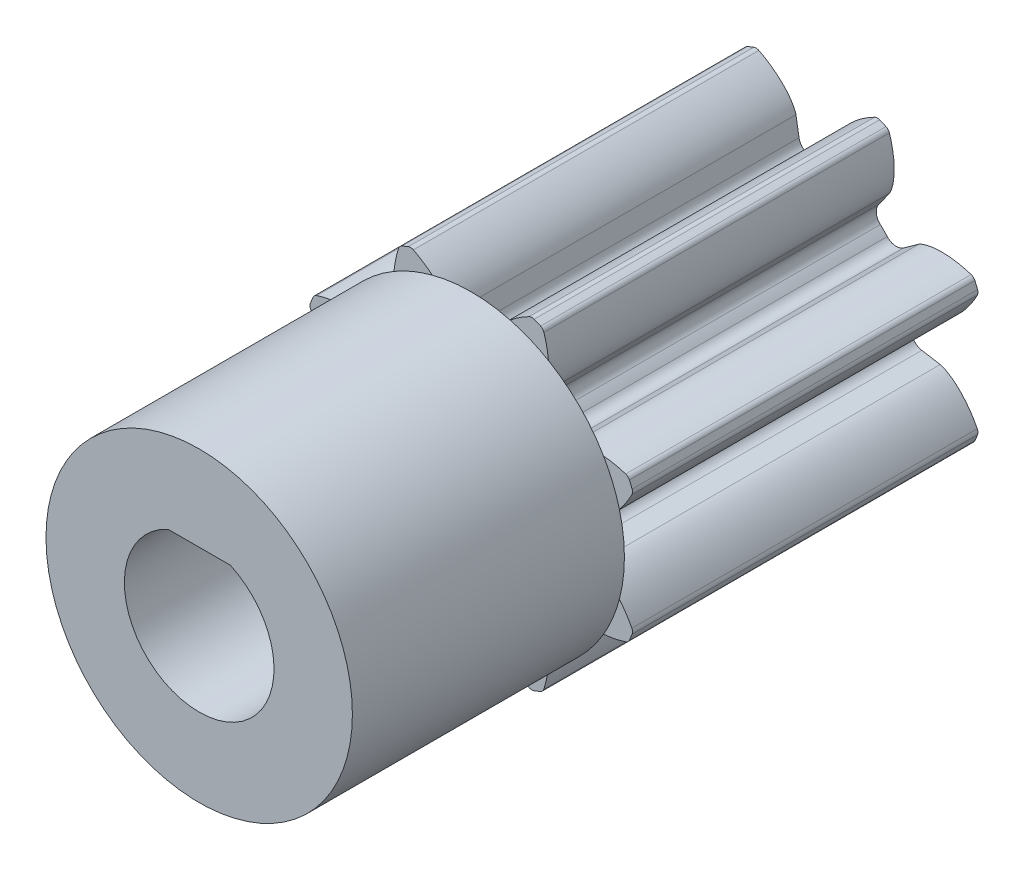
SolidWorks part; units mm, degrees
material "Alloy Steel"
ref_plane "Front" through (0, 0, 0) normal (0, 0, 1) x (1, 0, 0)
ref_plane "Top" through (0, 0, 0) normal (0, 1, 0) x (1, 0, 0)
ref_plane "Right" through (0, 0, 0) normal (1, 0, 0) x (0, 0, -1)
sketch "Sketch1" plane through (0, 0, 0) normal (0, 0, 1) x (1, 0, 0)
  circle A0 centre (0, 0) radius 6.35
extrude "Boss-Extrude1" add sketch "Sketch1" along normal blind 12.7
sketch "Sketch3" plane through (0, 0, 0) normal (0, 0, 1) x (1, 0, 0)
  line L0 (0, 0) -> (43.7181, 0) construction
  line L2 (0, 0) -> (-0.5784, 3.4443) construction
  line L3 (0, 0) -> (0.5784, 3.4443) construction
  line L4 (0.5784, 3.4443) -> (0.7625, 4.5405) construction
  line L5 (0, 0) -> (0, 61.276) construction
  line L6 (-0.5784, 3.4443) -> (-0.7625, 4.5405) construction
  circle A0 centre (0, 0) radius 6.35 construction
  circle A1 centre (0, 0) radius 5.08 construction
  circle A2 centre (0, 0) radius 4.604 construction
  arc A3 (0.5784, 3.4443) -> (-0.5784, 3.4443) centre (0, 0) ccw construction
  arc A5 (2.2164, 5.9506) -> (-2.2164, 5.9506) centre (0, 0) ccw
  spline S0 degree 4 poles (-0.7625, 4.5405) (-0.763, 4.5435) (-0.7648, 4.5519) (-0.7689, 4.5677) (-0.7767, 4.5932) (-0.7881, 4.6252) (-0.8045, 4.666) (-0.826, 4.7133) (-0.852, 4.7644) (-0.8825, 4.8189) (-0.9151, 4.8722) (-0.9496, 4.9244) (-0.9856, 4.9755) (-1.0311, 5.0363) (-1.0885, 5.1074) (-1.1594, 5.1881) (-1.2442, 5.2764) (-1.3353, 5.3629) (-1.4285, 5.4451) (-1.5269, 5.5244) (-1.6249, 5.5987) (-1.7306, 5.6719) (-1.8302, 5.7375) (-1.9458, 5.8065) (-2.0404, 5.8609) (-2.1692, 5.9277) (-2.2466, 5.9657) (-2.3384, 6.0084) (-2.3799, 6.0264) (-2.4054, 6.0376) knots 0 0 0 0 0 0.005377 0.015084 0.028532 0.04661 0.064855 0.092111 0.119476 0.146842 0.174209 0.201575 0.228941 0.256307 0.307035 0.361767 0.4165 0.471232 0.525964 0.580697 0.635429 0.690161 0.744894 0.799626 0.854358 0.909091 0.954545 1 1 1 1 1 construction
  spline S1 degree 4 poles (-0.7625, 4.5405) (-0.763, 4.5435) (-0.7648, 4.5519) (-0.7689, 4.5677) (-0.7767, 4.5932) (-0.7881, 4.6252) (-0.8045, 4.666) (-0.826, 4.7133) (-0.852, 4.7644) (-0.8825, 4.8189) (-0.9151, 4.8722) (-0.9496, 4.9244) (-0.9856, 4.9755) (-1.0311, 5.0363) (-1.0885, 5.1074) (-1.1594, 5.1881) (-1.2442, 5.2764) (-1.3353, 5.3629) (-1.4285, 5.4451) (-1.5269, 5.5244) (-1.6249, 5.5987) (-1.7306, 5.6719) (-1.8302, 5.7375) (-1.9458, 5.8065) (-2.0404, 5.8609) (-2.1413, 5.9133) (-2.1909, 5.9381) (-2.2164, 5.9506) knots 0 0 0 0 0 0.005377 0.015084 0.028532 0.04661 0.064855 0.092111 0.119476 0.146842 0.174209 0.201575 0.228941 0.256307 0.307035 0.361767 0.4165 0.471232 0.525964 0.580697 0.635429 0.690161 0.744894 0.799626 0.854358 0.909091 0.909091 0.909091 0.909091 0.909091
  spline S2 degree 4 poles (0.7625, 4.5405) (0.763, 4.5435) (0.7648, 4.5519) (0.7689, 4.5677) (0.7767, 4.5932) (0.7881, 4.6252) (0.8045, 4.666) (0.826, 4.7133) (0.852, 4.7644) (0.8825, 4.8189) (0.9151, 4.8722) (0.9496, 4.9244) (0.9856, 4.9755) (1.0311, 5.0363) (1.0885, 5.1074) (1.1594, 5.1881) (1.2442, 5.2764) (1.3353, 5.3629) (1.4285, 5.4451) (1.5269, 5.5244) (1.6249, 5.5987) (1.7306, 5.6719) (1.8302, 5.7375) (1.9458, 5.8065) (2.0404, 5.8609) (2.1692, 5.9277) (2.2466, 5.9657) (2.3384, 6.0084) (2.3799, 6.0264) (2.4054, 6.0376) knots 0 0 0 0 0 0.005377 0.015084 0.028532 0.04661 0.064855 0.092111 0.119476 0.146842 0.174209 0.201575 0.228941 0.256307 0.307035 0.361767 0.4165 0.471232 0.525964 0.580697 0.635429 0.690161 0.744894 0.799626 0.854358 0.909091 0.954545 1 1 1 1 1 construction
  spline S3 degree 4 poles (0.7625, 4.5405) (0.763, 4.5435) (0.7648, 4.5519) (0.7689, 4.5677) (0.7767, 4.5932) (0.7881, 4.6252) (0.8045, 4.666) (0.826, 4.7133) (0.852, 4.7644) (0.8825, 4.8189) (0.9151, 4.8722) (0.9496, 4.9244) (0.9856, 4.9755) (1.0311, 5.0363) (1.0885, 5.1074) (1.1594, 5.1881) (1.2442, 5.2764) (1.3353, 5.3629) (1.4285, 5.4451) (1.5269, 5.5244) (1.6249, 5.5987) (1.7306, 5.6719) (1.8302, 5.7375) (1.9458, 5.8065) (2.0404, 5.8609) (2.1413, 5.9133) (2.1909, 5.9381) (2.2164, 5.9506) knots 0 0 0 0 0 0.005377 0.015084 0.028532 0.04661 0.064855 0.092111 0.119476 0.146842 0.174209 0.201575 0.228941 0.256307 0.307035 0.361767 0.4165 0.471232 0.525964 0.580697 0.635429 0.690161 0.744894 0.799626 0.854358 0.909091 0.909091 0.909091 0.909091 0.909091
  point P0 (0, 3.4925)
sketch "DCLTBC" plane through (0, 0, 0) normal (0, 0, 1) x (1, 0, 0)
  line L0 (0, 0) -> (41.04, 0) construction
  line L1 (-0.5784, 3.4443) -> (-0.7625, 4.5405) construction
  line L2 (0.5784, 3.4443) -> (0.7625, 4.5405) construction
  line L3 (-0.5784, 3.4443) -> (-0.7625, 4.5405)
  line L4 (0.5784, 3.4443) -> (0.7625, 4.5405)
  line L5 (0, 0) -> (0, 104.9356) construction
  circle A0 centre (0, 0) radius 6.35
  circle A1 centre (0, 0) radius 5.08 construction
  circle A2 centre (0, 0) radius 4.604 construction
  arc A3 (0.5784, 3.4443) -> (-0.5784, 3.4443) centre (0, 0) ccw construction
  arc A4 (0.5784, 3.4443) -> (-0.5784, 3.4443) centre (0, 0) ccw
  spline S0 degree 4 poles (-985.3765, -170.0538) (-13.2322, 1.3996) (-0.8474, 3.8586) (-0.6755, 4.2604) (-0.7767, 4.5932) (-0.7881, 4.6252) (-0.8045, 4.666) (-0.826, 4.7133) (-0.852, 4.7644) (-0.8825, 4.8189) (-0.9151, 4.8722) (-0.9496, 4.9244) (-0.9856, 4.9755) (-1.0311, 5.0363) (-1.0885, 5.1074) (-1.1594, 5.1881) (-1.2442, 5.2764) (-1.3353, 5.3629) (-1.4285, 5.4451) (-1.5269, 5.5244) (-1.6249, 5.5987) (-1.7306, 5.6719) (-1.8302, 5.7375) (-1.9458, 5.8065) (-2.4469, 6.0948) (-4.2835, 6.892) (20.1681, -5.2427) (-900.8438, 444.5764) knots -0.5622 -0.5622 -0.5622 -0.5622 -0.5622 0.005377 0.015084 0.028532 0.04661 0.064855 0.092111 0.119476 0.146842 0.174209 0.201575 0.228941 0.256307 0.307035 0.361767 0.4165 0.471232 0.525964 0.580697 0.635429 0.690161 0.744894 0.799626 0.854358 1.850205 1.850205 1.850205 1.850205 1.850205 only from (-0.7625, 4.5405) to (-2.2164, 5.9506) construction
  spline S1 degree 4 poles (985.3765, -170.0538) (13.2322, 1.3996) (0.8474, 3.8586) (0.6755, 4.2604) (0.7767, 4.5932) (0.7881, 4.6252) (0.8045, 4.666) (0.826, 4.7133) (0.852, 4.7644) (0.8825, 4.8189) (0.9151, 4.8722) (0.9496, 4.9244) (0.9856, 4.9755) (1.0311, 5.0363) (1.0885, 5.1074) (1.1594, 5.1881) (1.2442, 5.2764) (1.3353, 5.3629) (1.4285, 5.4451) (1.5269, 5.5244) (1.6249, 5.5987) (1.7306, 5.6719) (1.8302, 5.7375) (1.9458, 5.8065) (2.4469, 6.0948) (4.2835, 6.892) (-20.1681, -5.2427) (900.8438, 444.5764) knots -0.5622 -0.5622 -0.5622 -0.5622 -0.5622 0.005377 0.015084 0.028532 0.04661 0.064855 0.092111 0.119476 0.146842 0.174209 0.201575 0.228941 0.256307 0.307035 0.361767 0.4165 0.471232 0.525964 0.580697 0.635429 0.690161 0.744894 0.799626 0.854358 1.850205 1.850205 1.850205 1.850205 1.850205 only from (0.7625, 4.5405) to (2.2164, 5.9506) construction
  spline S2 degree 4 poles (-0.7625, 4.5405) (-0.763, 4.5435) (-0.7648, 4.5519) (-0.7689, 4.5677) (-0.7767, 4.5932) (-0.7881, 4.6252) (-0.8045, 4.666) (-0.826, 4.7133) (-0.852, 4.7644) (-0.8825, 4.8189) (-0.9151, 4.8722) (-0.9496, 4.9244) (-0.9856, 4.9755) (-1.0311, 5.0363) (-1.0885, 5.1074) (-1.1594, 5.1881) (-1.2442, 5.2764) (-1.3353, 5.3629) (-1.4285, 5.4451) (-1.5269, 5.5244) (-1.6249, 5.5987) (-1.7306, 5.6719) (-1.8302, 5.7375) (-1.9458, 5.8065) (-2.0404, 5.8609) (-2.1413, 5.9133) (-2.1909, 5.9381) (-2.2164, 5.9506) knots 0 0 0 0 0 0.005377 0.015084 0.028532 0.04661 0.064855 0.092111 0.119476 0.146842 0.174209 0.201575 0.228941 0.256307 0.307035 0.361767 0.4165 0.471232 0.525964 0.580697 0.635429 0.690161 0.744894 0.799626 0.854358 0.909091 0.909091 0.909091 0.909091 0.909091
  spline S3 degree 4 poles (0.7625, 4.5405) (0.763, 4.5435) (0.7648, 4.5519) (0.7689, 4.5677) (0.7767, 4.5932) (0.7881, 4.6252) (0.8045, 4.666) (0.826, 4.7133) (0.852, 4.7644) (0.8825, 4.8189) (0.9151, 4.8722) (0.9496, 4.9244) (0.9856, 4.9755) (1.0311, 5.0363) (1.0885, 5.1074) (1.1594, 5.1881) (1.2442, 5.2764) (1.3353, 5.3629) (1.4285, 5.4451) (1.5269, 5.5244) (1.6249, 5.5987) (1.7306, 5.6719) (1.8302, 5.7375) (1.9458, 5.8065) (2.0404, 5.8609) (2.1413, 5.9133) (2.1909, 5.9381) (2.2164, 5.9506) knots 0 0 0 0 0 0.005377 0.015084 0.028532 0.04661 0.064855 0.092111 0.119476 0.146842 0.174209 0.201575 0.228941 0.256307 0.307035 0.361767 0.4165 0.471232 0.525964 0.580697 0.635429 0.690161 0.744894 0.799626 0.854358 0.909091 0.909091 0.909091 0.909091 0.909091
extrude "Cut-Extrude-DCLTBC" cut sketch "DCLTBC" along normal through all
fillet "Fillet-Tip-DCLTBC" radius 0.2258 2 edges at (2.2164, 5.9506, 6.35) (-2.2164, 5.9506, 6.35)
fillet "Fillet-Root-DCLTBC" radius 0.4517 2 edges at (-0.5784, 3.4443, 6.35) (0.5784, 3.4443, 6.35)
pattern_circular "CirPattern-DCLTBC" count 8 over 360 about axis through (0, 0, 12.7) along (0, 0, 1) of "Cut-Extrude-DCLTBC", "Fillet-Tip-DCLTBC", "Fillet-Root-DCLTBC"
sketch "Sketch4" plane through (0, 0, 12.7) normal (0, 0, 1) x (1, 0, 0)
  circle A0 centre (0, 0) radius 5.6319
  dimension "D1" = 11.2639
extrude "Boss-Extrude2" add sketch "Sketch4" along normal blind 10
sketch "Sketch5" plane through (0, 0, 0) normal (0, 0, -1) x (-1, 0, 0)
  line L0 (-1.1456, 2.5) -> (1.1456, 2.5)
  circle A0 centre (0, 0) radius 2.75
  dimension "D1" = 5.5
  dimension "D2" = 2.5
extrude "Cut-Extrude1" cut sketch "Sketch5" against normal through all contours L0 A0
equation "\"DiametralPitch\"= 20'Diametral Pitch"
equation "\"NumTeeth\"= 8'Number of Teeth"
equation "\"PressureAngle\"= 25deg'Pressure Angle"
equation "\"Addendum\"= 1 / \"DiametralPitch\"'Addendum"
equation "\"Dedendum\"= 1.25 / \"DiametralPitch\"'Dedendum"
equation "\"WorkingDepth\"= 2 / \"DiametralPitch\"'Working Depth - here for REF (Not used in building model)"
equation "\"WholeDepth\"= 2.25 / \"DiametralPitch\"'Whole Depth - here for REF (Not used in building model)"
equation "\"Clearance\"= .25 / \"DiametralPitch\"'Clearance"
equation "\"CircularPitch\"= pi / \"DiametralPitch\"'Circular Pitch - here for REF (Not used in building model)"
equation "\"PitchCircle\"= \"NumTeeth\" / \"DiametralPitch\"'Pitch Circle - or - Pitch Diameter"
equation "\"OutsideDiameter\"= ( \"NumTeeth\" + 2 ) / \"DiametralPitch\"'Outside Diameter"
equation "\"Fillet_Root\"= \"Clearance\" * cos ( \"PressureAngle\" ) * tan ( ( 90 + \"PressureAngle\" ) / 2 ) 'Fillet Root"
equation "\"AddendumCircle\"= \"PitchCircle\" + ( 2 * \"Addendum\" )'Addendum Circle - or - Addendum Diameter"
equation "\"DedendumCircle\"= \"PitchCircle\" - ( 2 * \"Dedendum\" )'Dedendum Circle - or - Dedendum Diameter"
equation "\"BaseCircle\"= \"PitchCircle\" * cos ( \"PressureAngle\" )'Base Circle - Base Diameter"
equation "\"PitchAngle\"= 360deg / \"NumTeeth\"'Pitch Angle"
equation "\"Alpha\"= sqr ( \"PitchCircle\" ^ 2 - \"BaseCircle\" ^ 2 ) / \"BaseCircle\" * 180 / PI - \"PressureAngle\"'Alpha - Used for Calculating Beta"
equation "\"Beta\"= ( \"PitchAngle\" / 4 - ( \"Alpha\" - 90 ) )'Beta - Used in definition of the parameters for the parametric equation driven curve"
equation "\"Gamma\"= ( \"PitchAngle\" / 4 - ( \"Alpha\" + 90 ) )'Gamma - Used in definition of the parameters for the parametric equation driven curve"
equation "\"Phi\"= sqr ( ( \"AddendumCircle\" / 2 ) ^ 2 - ( \"BaseCircle\" / 2 ) ^ 2 ) / ( \"BaseCircle\" / 2 )'Phi - Used in definition of the parameters for the parametric equation driven curve"
equation "\"DCGTBC\"= iif ( \"DedendumCircle\" > \"BaseCircle\" , \"unsuppressed\" , \"suppressed\" )'if Dedendum Circle IS GREATER THAN BaseCircle THEN UnsuppressORSuppress FEATURE"
equation "\"DCLTBC\"= iif ( \"DedendumCircle\" - .002 > \"BaseCircle\" , \"suppressed\" , \"unsuppressed\" )'if Dedendum Circle - .002 IS GREATER THAN BaseCircle THEN SuppressORUnsuppress FEATURE"
equation "\"Cut-Extrude-DCGTBC\"= iif ( \"DedendumCircle\" > \"BaseCircle\" , \"unsuppressed\" , \"suppressed\" )'if Dedendum Circle IS GREATER THAN BaseCircle THEN UnsuppressORSuppress FEATURE"
equation "\"Cut-Extrude-DCLTBC\"= iif ( \"DedendumCircle\" - .002 > \"BaseCircle\" , \"suppressed\" , \"unsuppressed\" )'if Dedendum Circle - .002 IS GREATER THAN BaseCircle THEN SuppressORUnsuppress FEATURE"
equation "\"CirPattern-DCGTBC\"= iif ( \"DedendumCircle\" > \"BaseCircle\" , \"unsuppressed\" , \"suppressed\" )'if Dedendum Circle IS GREATER THAN BaseCircle THEN UnsuppressORSuppress FEATURE"
equation "\"CirPattern-DCLTBC\"= iif ( \"DedendumCircle\" - .002 > \"BaseCircle\" , \"suppressed\" , \"unsuppressed\" )'if Dedendum Circle - .002 IS GREATER THAN BaseCircle THEN SuppressORUnsuppress FEATURE"
equation "\"Fillet-Tip-DCGTBC\"= iif ( \"DedendumCircle\" > \"BaseCircle\" , \"unsuppressed\" , \"suppressed\" )'if Dedendum Circle IS GREATER THAN BaseCircle THEN UnsuppressORSuppress FEATURE"
equation "\"Fillet-Tip-DCLTBC\"= iif ( \"DedendumCircle\" - .002 > \"BaseCircle\" , \"suppressed\" , \"unsuppressed\" )'if Dedendum Circle - .002 IS GREATER THAN BaseCircle THEN SuppressORUnsuppress FEATURE"
equation "\"Fillet-Root-DCLTBC\"= iif ( \"DedendumCircle\" - .002 > \"BaseCircle\" , \"suppressed\" , \"unsuppressed\" )'if Dedendum Circle - .002 IS GREATER THAN BaseCircle THEN SuppressORUnsuppress FEATURE"
equation "\"D1\" = \"NumTeeth\"'Number of Teeth"
equation "\"D1@CirPattern-DCLTBC\"= \"NumTeeth\"'Number of Teeth"
equation "\"D1\" = \"Fillet_Root\" / 2'Tip Rad For Large No of Teeth"
equation "\"D1@Fillet-Tip-DCLTBC\"=\"Fillet_Root\" / 2'Tip Rad For Small No of Teeth"
equation "\"D1@Fillet-Root-DCLTBC\"= \"Fillet_Root\"'Fillet Root"
